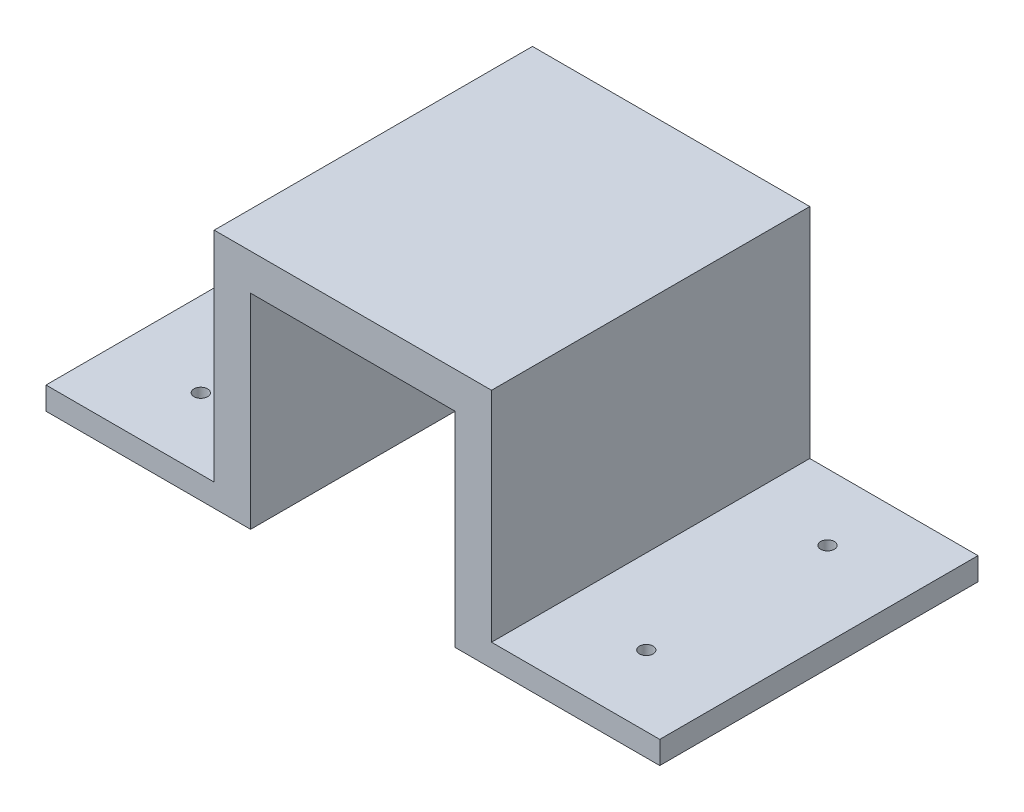
SolidWorks part; units mm, degrees
ref_plane "Front" through (0, 0, 0) normal (0, 0, 1) x (1, 0, 0)
ref_plane "Top" through (0, 0, 0) normal (0, 1, 0) x (1, 0, 0)
ref_plane "Right" through (0, 0, 0) normal (1, 0, 0) x (0, 0, -1)
sketch "Sketch1" plane through (0, 0, 0) normal (0, 0, 1) x (1, 0, 0)
  line L0 (-68.9516, 0) -> (-23.9516, 0)
  line L1 (-23.9516, 0) -> (-23.9516, 45)
  line L2 (-23.9516, 45) -> (21.0484, 45)
  line L3 (21.0484, 45) -> (21.0484, 0)
  line L4 (21.0484, 0) -> (66.0484, 0)
  line L5 (66.0484, 0) -> (66.0484, 5)
  line L6 (66.0484, 5) -> (29.0484, 5)
  line L7 (29.0484, 5) -> (29.0484, 53)
  line L8 (29.0484, 53) -> (-31.9516, 53)
  line L9 (-31.9516, 53) -> (-31.9516, 5)
  line L10 (-31.9516, 5) -> (-68.9516, 5)
  line L11 (-68.9516, 5) -> (-68.9516, 0)
  point P3 (-31.9516, 29)
  dimension "D1" = 45
  dimension "D2" = 45
  dimension "D3" = 8
  dimension "D4" = 5
  dimension "D5" = 5
  dimension "D6" = 8
  dimension "D7" = 8
  dimension "D8" = 45
  dimension "D9" = 45
extrude "Boss-Extrude1" add sketch "Sketch1" along normal blind 70
sketch "Sketch6" plane through (0, 5, 0) normal (0, 1, 0) x (1, 0, 0)
  line L5 (-31.9516, -35) -> (-68.9516, -35) construction
  line L6 (-31.9516, -70) -> (-31.9516, 0) construction
  line L7 (-68.9516, -70) -> (-68.9516, 0) construction
  line L8 (-31.9516, -70) -> (-68.9516, -70) construction
  line L9 (-31.9516, 0) -> (-68.9516, 0) construction
  line L10 (-50.4516, 0) -> (-50.4516, -70) construction
  line L11 (47.5484, 0) -> (47.5484, -70) construction
  line L14 (66.0484, 0) -> (29.0484, 0) construction
  line L17 (66.0484, -70) -> (29.0484, -70) construction
  line L18 (29.0484, -35) -> (66.0484, -35) construction
  line L19 (29.0484, -70) -> (29.0484, 0) construction
  line L20 (66.0484, -70) -> (66.0484, 0) construction
  circle A0 centre (-50.4516, -14.6031) radius 1.5
  circle A1 centre (-50.4516, -54.4555) radius 1.5
  circle A2 centre (47.5484, -14.6031) radius 1.5
  circle A3 centre (47.5484, -54.4555) radius 1.5
  point P3 (-68.9516, -35)
  point P33 (0, 0)
  point P34 (0, 0)
extrude "Cut-Extrude1" cut sketch "Sketch6" against normal blind 70
